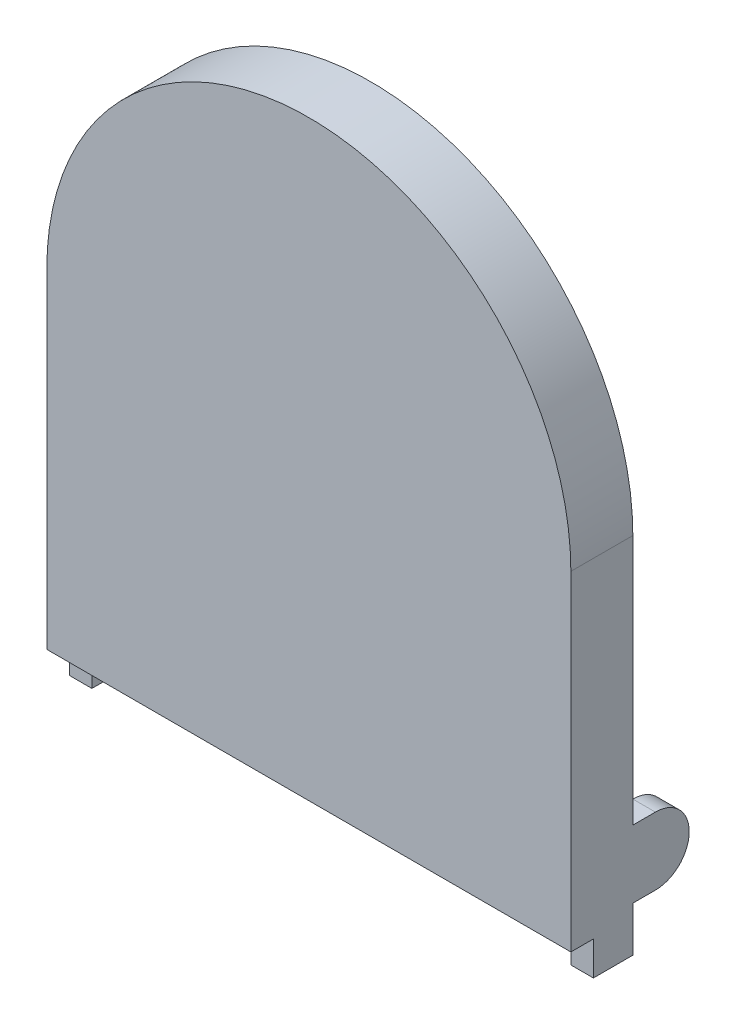
SolidWorks part; units mm, degrees
ref_plane "Front Plane" through (0, 0, 0) normal (0, 0, 1) x (1, 0, 0)
ref_plane "Top Plane" through (0, 0, 0) normal (0, 1, 0) x (1, 0, 0)
ref_plane "Right Plane" through (0, 0, 0) normal (1, 0, 0) x (0, 0, -1)
sketch "Sketch1" plane through (0, 0, 0) normal (0, 0, 1) x (1, 0, 0)
  line L1 (42.5, 0) -> (42.5, 32.25)
  line L2 (0, 0) -> (0, 32.25)
  line L3 (21.25, 0) -> (21.25, 53.5) construction
  line L4 (0, 0) -> (42.5, 0) construction
  line L5 (-2, 0) -> (-2, 32.25)
  line L6 (44.5, 0) -> (44.5, 32.25)
  line L7 (-2, 0) -> (0, 0)
  line L8 (42.5, 0) -> (44.5, 0)
  arc A0 (0, 32.25) -> (42.5, 32.25) centre (21.25, 32.25) cw
  arc A1 (-2, 32.25) -> (44.5, 32.25) centre (21.25, 32.25) cw
  dimension "D1" = 53.5
  dimension "D2" = 42.5
  dimension "D4" = 32.25
  dimension "D3" = 2
extrude "Boss-Extrude1" add sketch "Sketch1" along normal blind 3.5
sketch "Sketch2" plane through (0, 0, 3.5) normal (0, 0, 1) x (1, 0, 0)
  line L0 (-2, 3) -> (44.5, 3)
  line L1 (-2, 32.25) -> (-2, 0) construction
  line L2 (44.5, 0) -> (44.5, 32.25) construction
  line L3 (44.5, 3) -> (44.5, 32.25)
  line L4 (-2, 3) -> (-2, 32.25)
  line L5 (-2, 0) -> (0, 0) construction
  arc A0 (-2, 32.25) -> (44.5, 32.25) centre (21.25, 32.25) cw
  dimension "D1" = 3
extrude "Boss-Extrude2" add sketch "Sketch2" along normal blind 2
sketch "Sketch3" plane through (-2, 0, 0) normal (-1, 0, 0) x (0, 0, 1)
  line L0 (0, 4) -> (-2, 4)
  line L1 (0, 32.25) -> (0, 0) construction
  line L2 (0, 10) -> (-2, 10)
  line L3 (0, 10) -> (0, 4)
  line L4 (3.5, 0) -> (0, 0) construction
  arc A0 (-2, 4) -> (-2, 10) centre (-2, 7) cw
  point P7 (-5, 7)
  dimension "D1" = 6
  dimension "D2" = 5
  dimension "D3" = 4
  dimension "D4" = 7
extrude "Boss-Extrude3" add sketch "Sketch3" against normal blind 2
sketch "Sketch4" plane through (0, 0, 0) normal (1, 0, 0) x (0, 0, -1)
  line L0 (-3.5, 0) -> (0, 0) construction
  circle A0 centre (2, 7) radius 1.5
  arc A1 (2, 4) -> (2, 10) centre (2, 7) ccw construction
  point P10 (-13.0512, 6.2491)
  dimension "D1" = 3
  dimension "D2" = 0
  dimension "D3" = 3
  dimension "D4" = 7
extrude "Boss-Extrude4" add sketch "Sketch4" along normal blind 1.5
fillet "Fillet1" radius 1 1 edges at (1.5, 7, -3.5)
ref_plane "Plane1" through (21.25, 0, 0) normal (1, 0, 0) x (0, 0, -1)
mirror "Mirror1" about plane through (21.25, 0, 0) normal (1, 0, 0) of "Boss-Extrude3", "Fillet1", "Boss-Extrude4", "Boss-Extrude1"
